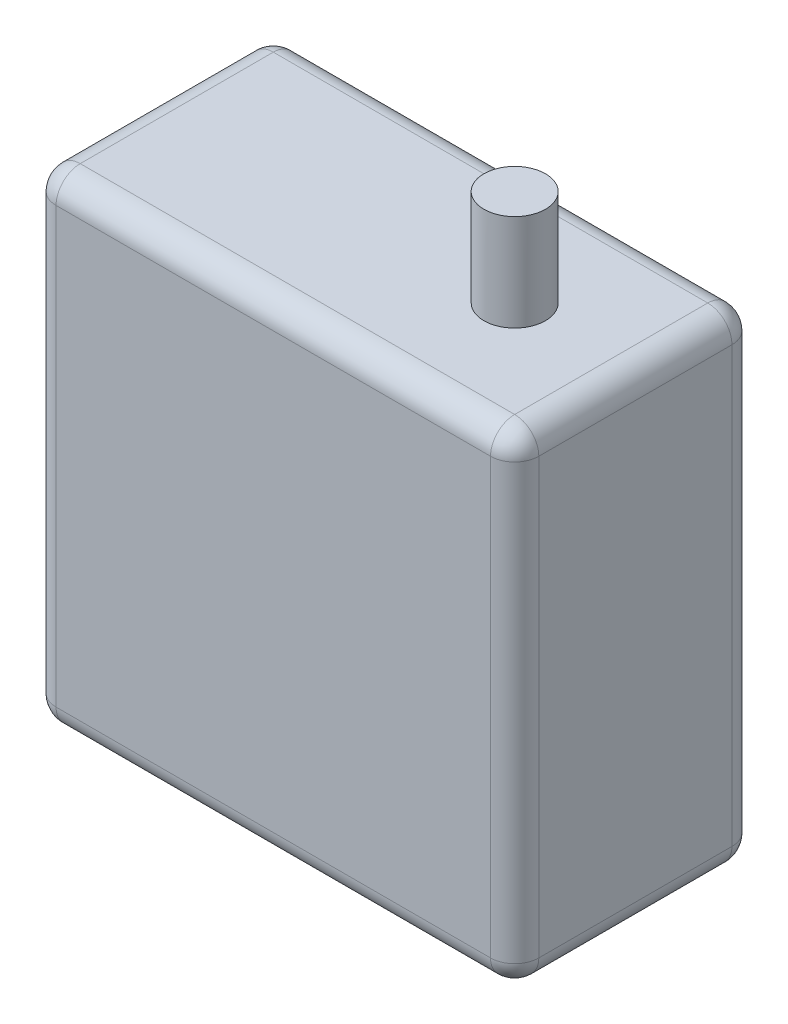
SolidWorks part; units mm, degrees
ref_plane "前视基准面" through (0, 0, 0) normal (0, 0, 1) x (1, 0, 0)
ref_plane "上视基准面" through (0, 0, 0) normal (0, 1, 0) x (1, 0, 0)
ref_plane "右视基准面" through (0, 0, 0) normal (1, 0, 0) x (0, 0, -1)
other "Configuration Table"
sketch "草图1" plane through (0, 0, 0) normal (0, 1, 0) x (1, 0, 0)
  line L1 (-20, -10) -> (20, -10)
  line L2 (-20, -10) -> (-20, 10)
  line L3 (-20, 10) -> (20, 10)
  line L4 (20, -10) -> (20, 10)
  line L5 (-20, -10) -> (20, 10) construction
  line L6 (-20, 10) -> (20, -10) construction
  point P0 (0, 0)
  dimension "D1" = 20
  dimension "D2" = 40
extrude "凸台-拉伸1" add sketch "草图1" along normal blind 40
sketch "草图2" plane through (0, 40, 0) normal (0, 1, 0) x (1, 0, 0)
  line L0 (-1000, 0) -> (49000, 0) construction
  circle A0 centre (10, 0) radius 2.55
  point P3 (0, 0)
  dimension "D1" = 5.1
  dimension "D2" = 10
extrude "凸台-拉伸2" add sketch "草图2" along normal blind 8
fillet "圆角1" radius 2 12 edges at (-20, 20, -10) (-20, 40, 0) (-20, 20, 10) (0, 0, -10) (-20, 0, 0) (0, 0, 10) (20, 0, 0) (0, 40, 10) (0, 40, -10) (20, 40, 0) (20, 20, 10) (20, 20, -10)
